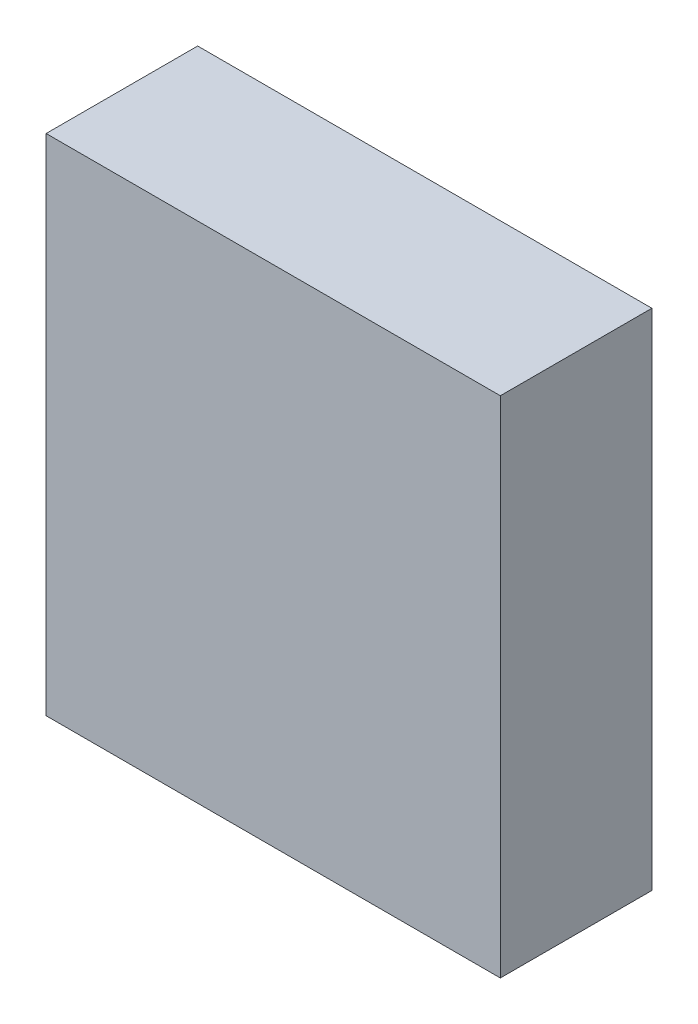
SolidWorks part; units mm, degrees
ref_plane "Front Plane" through (0, 0, 0) normal (0, 0, 1) x (1, 0, 0)
ref_plane "Top Plane" through (0, 0, 0) normal (0, 1, 0) x (1, 0, 0)
ref_plane "Right Plane" through (0, 0, 0) normal (1, 0, 0) x (0, 0, -1)
sketch "Sketch1" plane through (0, 0, 0) normal (0, 0, 1) x (1, 0, 0)
  line L0 (-1.4986, 1.6256) -> (1.4986, 1.6256)
  line L1 (1.4986, 1.6256) -> (1.4986, -1.7018)
  line L2 (1.4986, -1.7018) -> (-1.4986, -1.7018)
  line L3 (-1.4986, -1.7018) -> (-1.4986, 1.6256)
extrude "Component_Outline" add sketch "Sketch1" along normal blind 1 separate body
sketch3d "3DSketch1"
  line L0 (0, 0, 0) -> (1, 0, 0)
  line L1 (0, 0, 0) -> (0, 1, 0)
  line L2 (0, 0, 0) -> (0, 0, 1)
  point P0 (0, 0, 0)
